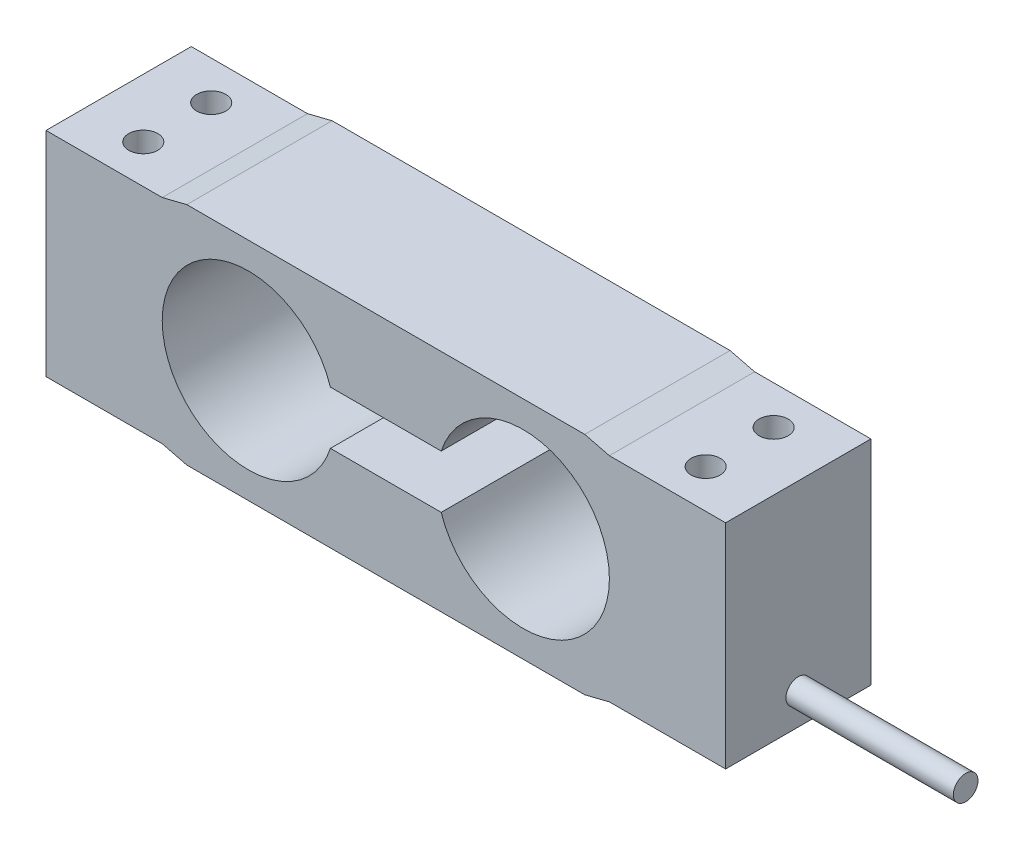
SolidWorks part; units mm, degrees
material "6061-T4 (SS)"
ref_plane "Front Plane" through (0, 0, 0) normal (0, 0, 1) x (1, 0, 0)
ref_plane "Top Plane" through (0, 0, 0) normal (0, 1, 0) x (1, 0, 0)
ref_plane "Right Plane" through (0, 0, 0) normal (1, 0, 0) x (0, 0, -1)
sketch "Sketch1" plane through (0, 0, 0) normal (0, 1, 0) x (1, 0, 0)
  line L1 (0, 0) -> (-70.104, 0)
  line L2 (0, 0) -> (0, 14.986)
  line L3 (0, 14.986) -> (-70.104, 14.986)
  line L4 (-70.104, 0) -> (-70.104, 14.986)
  dimension "D1" = 14.986
  dimension "D2" = 70.104
extrude "Boss-Extrude1" add sketch "Sketch1" along normal blind 21.9964
sketch "Sketch3" plane through (0, 0, 0) normal (0, 0, 1) x (1, 0, 0)
  line L0 (-35.052, 21.9964) -> (-35.052, 0) construction
  line L1 (-70.104, 21.9964) -> (0, 21.9964) construction
  line L2 (-70.104, 0) -> (0, 0) construction
  line L3 (-35.052, 10.9982) -> (-70.104, 10.9982) construction
  line L4 (-70.104, 21.9964) -> (-70.104, 0) construction
  line L5 (-58.1152, 21.9964) -> (-58.1152, 0) construction
  line L6 (-29.337, 13.7352) -> (-40.767, 13.7352)
  line L7 (-29.337, 8.2612) -> (-40.767, 8.2612)
  line L8 (-58.1152, 21.9964) -> (-55.5752, 21.3614)
  line L9 (-55.5752, 21.3614) -> (-14.5288, 21.3614)
  line L10 (-58.1152, 0) -> (-55.5752, 0.635)
  line L11 (-55.5752, 0.635) -> (-14.5288, 0.635)
  line L12 (-11.9888, 0) -> (-14.5288, 0.635)
  line L13 (-11.9888, 21.9964) -> (-14.5288, 21.3614)
  line L14 (-58.1152, 21.9964) -> (-11.9888, 21.9964)
  line L15 (-58.1152, 0) -> (-11.9888, 0)
  arc A0 (-40.767, 13.7352) -> (-40.767, 8.2612) centre (-49.2252, 10.9982) ccw
  arc A1 (-29.337, 13.7352) -> (-29.337, 8.2612) centre (-20.8788, 10.9982) cw
  point P18 (-35.052, 8.2612)
  point P20 (-35.052, 13.7352)
  point P26 (-35.052, 0.635)
  point P28 (-35.052, 21.3614)
  dimension "D2" = 17.78
  dimension "D1" = 11.9888
  dimension "D3" = 5.715
  dimension "D4" = 0.635
  dimension "D5" = 2.54
extrude "Cut-Extrude1" cut sketch "Sketch3" against normal through all
sketch "Sketch4" plane through (0, 21.9964, 0) normal (0, 1, 0) x (1, 0, 0)
  line L0 (-64.0588, 3.9878) -> (-64.0588, 10.9982) construction
  line L1 (-64.0588, 7.493) -> (-70.104, 7.493) construction
  line L2 (-70.104, 14.986) -> (-70.104, 0) construction
  line L3 (-35.052, 14.986) -> (-35.052, 0) construction
  line L4 (-55.5752, 14.986) -> (-14.5288, 14.986) construction
  line L5 (-55.5752, 0) -> (-14.5288, 0) construction
  circle A0 centre (-64.0588, 10.9982) radius 1.5
  circle A1 centre (-64.0588, 3.9878) radius 1.5
  circle A2 centre (-6.0452, 3.9878) radius 1.5
  circle A3 centre (-6.0452, 10.9982) radius 1.5
  dimension "D3" = 3
  dimension "D1" = 7.0104
  dimension "D2" = 58.0136
extrude "Cut-Extrude2" cut sketch "Sketch4" against normal through all
sketch "Sketch5" plane through (0, 0, 0) normal (1, 0, 0) x (0, 0, -1)
  line L0 (0, 0) -> (7.493, 3.2321) construction
  line L1 (7.493, 3.2321) -> (14.986, 0) construction
  circle A0 centre (7.493, 3.2321) radius 1.27
  dimension "D1" = 2.54
extrude "Boss-Extrude2" add sketch "Sketch5" along normal blind 17.272
sketch "Sketch6" plane through (0, 0, 0) normal (0, 0, 1) x (1, 0, 0)
  line L0 (-58.1152, 21.9964) -> (-55.5752, 21.3614)
  line L1 (-55.5752, 21.3614) -> (-14.5288, 21.3614)
  line L2 (-14.5288, 21.3614) -> (-11.9888, 21.9964)
  line L3 (-58.1152, 21.9964) -> (-11.9888, 21.9964) construction
  line L4 (-49.2252, 10.9982) -> (-20.8788, 10.9982) construction
  line L5 (-14.5288, 22.6314) -> (-11.9888, 21.9964)
  line L6 (-58.1152, 21.9964) -> (-55.5752, 22.6314)
  line L7 (-55.5752, 22.6314) -> (-14.5288, 22.6314)
  line L9 (-55.5752, -0.635) -> (-14.5288, -0.635)
  line L10 (-58.1152, 0) -> (-55.5752, -0.635)
  line L11 (-58.1152, 0) -> (-55.5752, 0.635)
  line L12 (-55.5752, 0.635) -> (-14.5288, 0.635)
  line L13 (-14.5288, 0.635) -> (-11.9888, 0)
  line L14 (-14.5288, -0.635) -> (-11.9888, 0)
extrude "Boss-Extrude3" add sketch "Sketch6" against normal through all
sketch "Sketch7" plane through (0, 0, -14.986) normal (0, 0, -1) x (-1, 0, 0)
  line L1 (0, 21.9964) -> (11.9888, 21.9964)
  line L2 (0, 21.9964) -> (0, 0)
  line L3 (0, 0) -> (11.9888, 0)
  line L4 (11.9888, 21.9964) -> (11.9888, 0)
extrude "Boss-Extrude4" add sketch "Sketch7" along normal blind 0.508 draft 45
